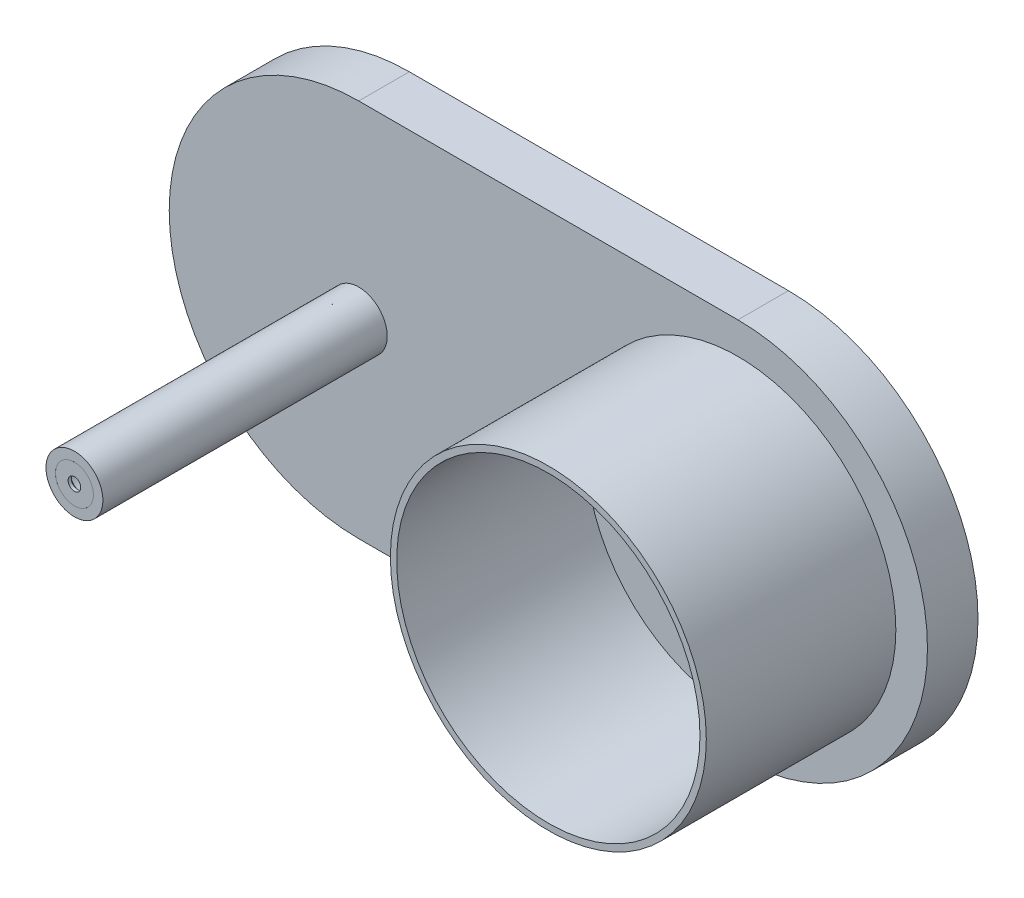
SolidWorks part; units mm, degrees
ref_plane "Front Plane" through (0, 0, 0) normal (0, 0, 1) x (1, 0, 0)
ref_plane "Top Plane" through (0, 0, 0) normal (0, 1, 0) x (1, 0, 0)
ref_plane "Right Plane" through (0, 0, 0) normal (1, 0, 0) x (0, 0, -1)
sketch "Sketch1" plane through (0, 0, 0) normal (0, 0, 1) x (1, 0, 0)
  line L0 (-30, 0) -> (30, 0) construction
  line L1 (55, 0) -> (-55, 0) construction
  line L2 (-30, 30) -> (30, 30)
  line L3 (-30, -30) -> (30, -30)
  arc A0 (-30, 30) -> (-30, -30) centre (-30, 0) ccw
  arc A1 (30, -30) -> (30, 30) centre (30, 0) ccw
  point P5 (0, 0)
  dimension "D1" = 30
  dimension "D2" = 60
  dimension "D3" = 0
extrude "Boss-Extrude1" add sketch "Sketch1" along normal blind 8
ref_plane "Plane1" through (0, 0, 0) normal (0, 1, 0) x (1, 0, 0)
sketch "Sketch2" plane through (0, 0, 0) normal (0, 1, 0) x (1, 0, 0)
  line L0 (-30, -4) -> (30, -4) construction
  line L1 (-30, -8) -> (-30, 0) construction
  line L2 (-30, -5.5) -> (30, -5.5)
  line L3 (-30, -5.5) -> (-30, -2.5)
  line L4 (-30, -2.5) -> (30, -2.5)
  line L5 (30, -5.5) -> (30, -2.5)
  line L6 (30, -8) -> (30, 0) construction
  line L7 (30, -5.5) -> (30, -7.9993) construction
  line L8 (-30, -5.5) -> (-30, -7.9993) construction
  dimension "D1" = 4
  dimension "D2" = 1.5
  dimension "D3" = 1.5
  dimension "D4" = 2.4993
extrude "Cut-Extrude1" cut sketch "Sketch2" against normal mid plane 8
sketch "Sketch3" plane through (0, 0, 8) normal (0, 0, 1) x (1, 0, 0)
  line L0 (-30, 0) -> (30, 0) construction
  circle A0 centre (30, 0) radius 4
  circle A1 centre (-30, 0) radius 3
  dimension "D1" = 8
  dimension "D2" = 6
extrude "Cut-Extrude3" cut sketch "Sketch3" against normal blind 5.5
sketch "Sketch4" plane through (0, 0, 8) normal (0, 0, 1) x (1, 0, 0)
  circle A0 centre (-30, 0) radius 4.5
  circle A2 centre (-30, 0) radius 3
  dimension "D1" = 9
  dimension "D2" = 6
extrude "Boss-Extrude3" add sketch "Sketch4" along normal blind 45
sketch "Sketch5" plane through (0, 0, 0) normal (0, 1, 0) x (1, 0, 0)
  line L0 (-25.5, -7.9993) -> (-25.5, -52.9993) construction
  line L1 (-25.5, -7.9993) -> (-30, -7.9993) construction
  line L2 (-25.5, -52.9993) -> (-27, -52.9993) construction
  line L3 (-34.5, -7.9993) -> (-34.5, -52.9993) construction
  line L4 (-34.5, -52.9993) -> (-33, -52.9993) construction
  line L6 (-34.5, -7.9993) -> (-31.4963, -7.9993) construction
  line L10 (-30, -53) -> (-30, -55.3868) construction
  line L11 (-33, -53) -> (-27, -53) construction
  line L13 (-33, -52.9993) -> (-33, -50.9993)
  line L14 (-33, -50.9993) -> (-31, -52.4993)
  line L16 (-31, -52.9993) -> (-31, -52.4993)
  line L17 (-33, -52.9993) -> (-31, -52.9993)
  dimension "D1" = 4.5
  dimension "D2" = 4.5
  dimension "D3" = 1.5
  dimension "D4" = 45
  dimension "D5" = 2
  dimension "D6" = 2.5
  dimension "D7" = 0.5
revolve "Revolve1" add sketch "Sketch5" angle 360 about L10
sketch "Sketch6" plane through (0, 0, 8) normal (0, 0, 1) x (1, 0, 0)
  line L0 (-30, 0) -> (30, 0) construction
  line L1 (29.15, 0) -> (-29.15, 0) construction
  circle A0 centre (30, 0) radius 25
  circle A1 centre (30, 0) radius 24
  point P7 (30, 0)
  point P9 (30, 0)
  dimension "D1" = 50
  dimension "D2" = 48
extrude "Boss-Extrude4" add sketch "Sketch6" along normal blind 30
equation "\"lin\"=45"
